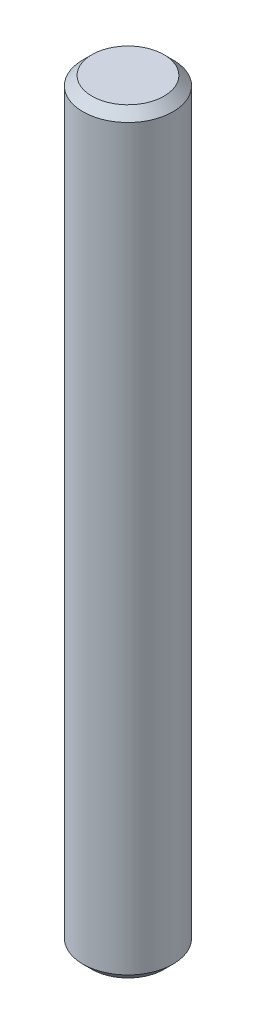
SolidWorks part; units mm, degrees
material "AISI 316 Annealed Stainless Steel Bar (SS)"
ref_plane "Front Plane" through (0, 0, 0) normal (0, 0, 1) x (1, 0, 0)
ref_plane "Top Plane" through (0, 0, 0) normal (0, 1, 0) x (1, 0, 0)
ref_plane "Right Plane" through (0, 0, 0) normal (1, 0, 0) x (0, 0, -1)
sketch "Sketch1" plane through (0, 0, 0) normal (0, 1, 0) x (1, 0, 0)
  circle A0 centre (0, 0) radius 3.175
  dimension "D1" = 6.35
extrude "Boss-Extrude1" add sketch "Sketch1" along normal blind 53.34
chamfer "Chamfer1" distance 0.635 angle 45 2 edges at (0, 0, 3.175) (0, 53.34, 3.175)
